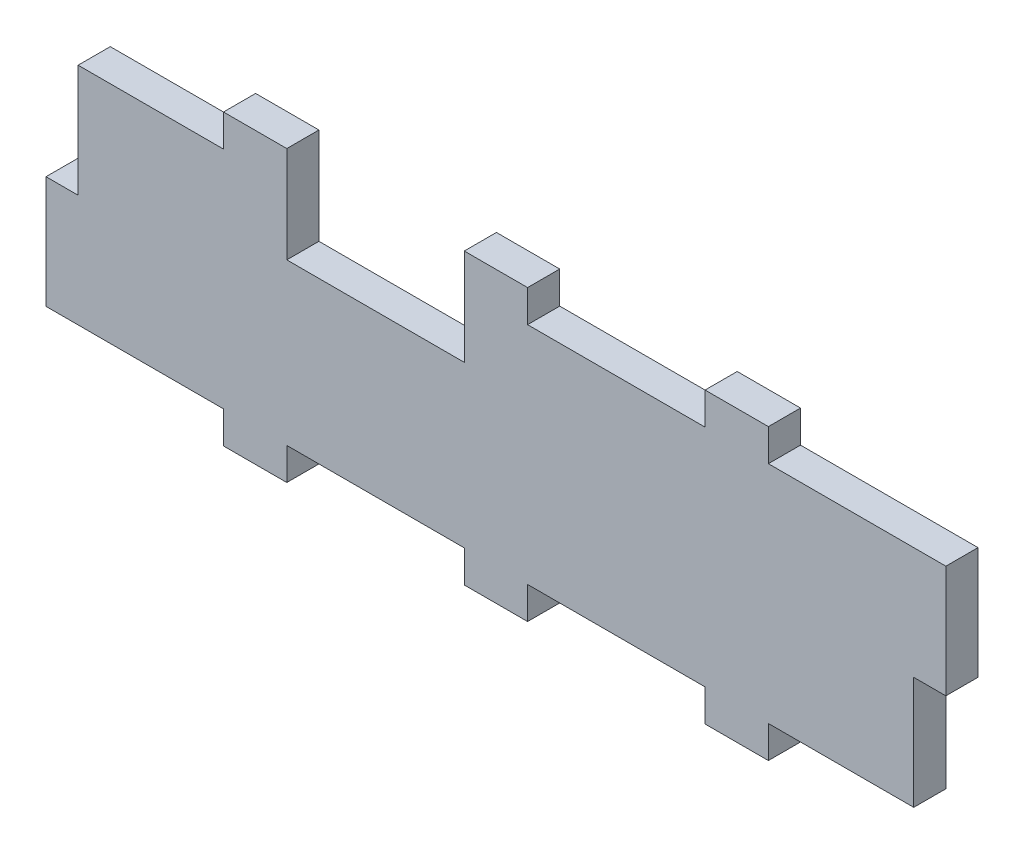
SolidWorks part; units mm, degrees
ref_plane "Front Plane" through (0, 0, 0) normal (0, 0, 1) x (1, 0, 0)
ref_plane "Top Plane" through (0, 0, 0) normal (0, 1, 0) x (1, 0, 0)
ref_plane "Right Plane" through (0, 0, 0) normal (1, 0, 0) x (0, 0, -1)
sketch "Sketch2" plane through (0, 0, 0) normal (0, 0, 1) x (1, 0, 0)
  line L0 (-42.3875, 22.5) -> (-42.3875, 17.5)
  line L1 (-65, -17.5) -> (65, -17.5)
  line L2 (-65, -17.5) -> (-65, 17.5)
  line L3 (-65, 17.5) -> (65, 17.5)
  line L4 (65, -17.5) -> (65, 17.5)
  line L5 (-65, -17.5) -> (65, 17.5) construction
  line L6 (-65, 17.5) -> (65, -17.5) construction
  line L7 (-65, -17.5) -> (-70, -17.5)
  line L8 (-65, -17.5) -> (-65, -0.025)
  line L9 (-65, -0.025) -> (-70, -0.025)
  line L10 (-70, -17.5) -> (-70, -0.025)
  line L11 (-42.3875, -17.5) -> (-32.5375, -17.5)
  line L12 (-42.3875, -17.5) -> (-42.3875, -22.5)
  line L13 (-42.3875, -22.5) -> (-32.5375, -22.5)
  line L14 (-32.5375, -17.5) -> (-32.5375, -22.5)
  line L15 (-4.925, -17.5) -> (4.925, -17.5)
  line L16 (-4.925, -17.5) -> (-4.925, -22.5)
  line L17 (-4.925, -22.5) -> (4.925, -22.5)
  line L18 (4.925, -17.5) -> (4.925, -22.5)
  line L19 (32.5375, -17.5) -> (42.3875, -17.5)
  line L20 (32.5375, -17.5) -> (32.5375, -22.5)
  line L21 (32.5375, -22.5) -> (42.3875, -22.5)
  line L22 (42.3875, -17.5) -> (42.3875, -22.5)
  line L23 (65, 17.5) -> (70, 17.5)
  line L24 (65, 17.5) -> (65, 0.025)
  line L25 (65, 0.025) -> (70, 0.025)
  line L26 (70, 17.5) -> (70, 0.025)
  line L27 (-42.3875, 22.5) -> (-32.5375, 22.5)
  line L28 (-32.5375, 22.5) -> (-32.5375, 17.5)
  line L29 (-42.3875, 17.5) -> (-32.5375, 17.5)
  line L30 (-4.925, 22.5) -> (-4.925, 17.5)
  line L31 (-4.925, 22.5) -> (4.925, 22.5)
  line L32 (4.925, 22.5) -> (4.925, 17.5)
  line L33 (-4.925, 17.5) -> (4.925, 17.5)
  line L34 (32.5375, 22.5) -> (32.5375, 17.5)
  line L35 (32.5375, 22.5) -> (42.3875, 22.5)
  line L36 (42.3875, 22.5) -> (42.3875, 17.5)
  line L37 (32.5375, 17.5) -> (42.3875, 17.5)
  line L38 (32.5375, -20) -> (4.925, -20) construction
  line L39 (-4.925, -20) -> (-32.5375, -20) construction
  line L42 (42.3875, -20) -> (70, -20) construction
  line L43 (70, -20) -> (70, 0.025) construction
  line L44 (-42.3875, -20) -> (-70, -20) construction
  line L45 (-70, -20) -> (-70, -17.5) construction
  point P0 (0, 0)
  dimension "D1" = 35
  dimension "D2" = 130
  dimension "D3" = 17.475
  dimension "D4" = 5
  dimension "D5" = 5
  dimension "D6" = 5
  dimension "D7" = 5
  dimension "D8" = 9.85
  dimension "D9" = 9.85
  dimension "D10" = 9.85
  dimension "D13" = 5
  dimension "D14" = 17.475
  dimension "D16" = 2
extrude "Boss-Extrude1" add sketch "Sketch2" along normal blind 5 contours L1 L4 L3 L2 | L10 L7 L2 L9 | L28 L27 L0 L3 | L32 L31 L30 L3 | L36 L35 L34 L3 | L26 L23 L4 L25 | L22 L1 L20 L21 | L18 L1 L16 L17 | L14 L1 L12 L13
sketch "Sketch3" plane through (0, 0, 0) normal (0, 0, -1) x (-1, 0, 0)
  line L0 (32.5375, 22.5) -> (32.5375, 17.5) construction
  line L1 (4.925, 17.5) -> (32.5375, 17.5)
  line L2 (4.925, 17.5) -> (4.925, 7.5)
  line L3 (4.925, 7.5) -> (32.5375, 7.5)
  line L4 (32.5375, 17.5) -> (32.5375, 7.5)
  dimension "D1" = 10
extrude "Cut-Extrude1" cut sketch "Sketch3" against normal through all
